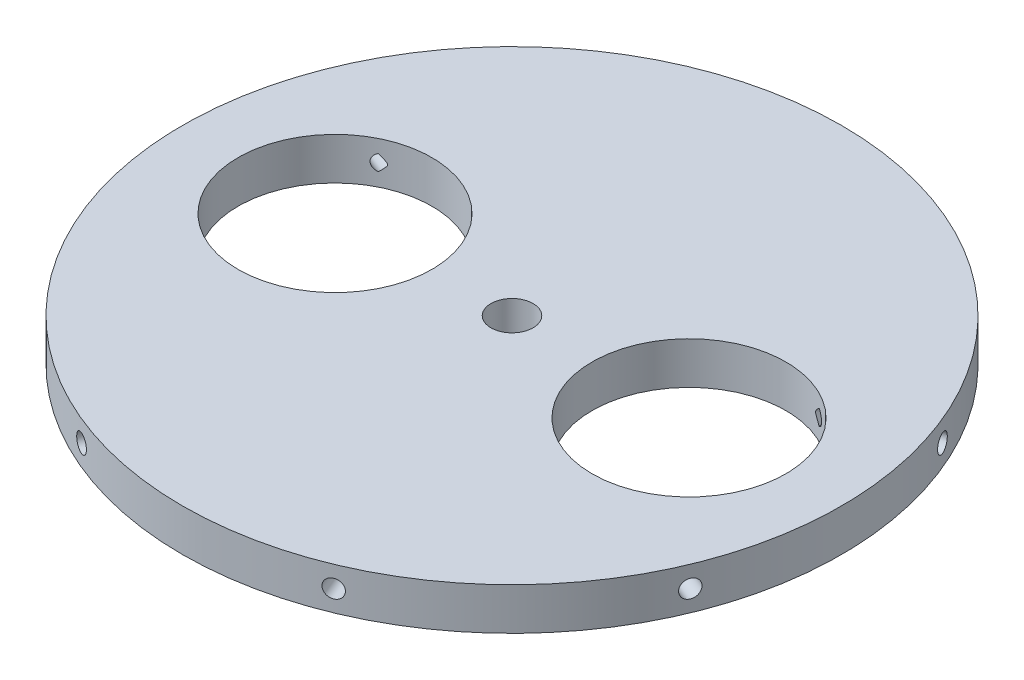
SolidWorks part; units mm, degrees
ref_plane "Front Plane" through (0, 0, 0) normal (0, 0, 1) x (1, 0, 0)
ref_plane "Top Plane" through (0, 0, 0) normal (0, 1, 0) x (1, 0, 0)
ref_plane "Right Plane" through (0, 0, 0) normal (1, 0, 0) x (0, 0, -1)
sketch "Sketch2" plane through (0, 0, 0) normal (0, 1, 0) x (1, 0, 0)
  circle A0 centre (0, 0) radius 49.657
  dimension "D1" = 99.314
extrude "Boss-Extrude1" add sketch "Sketch2" along normal blind 6.35
sketch "Sketch3" plane through (0, 6.35, 0) normal (0, 1, 0) x (1, 0, 0)
  line L0 (-56.3402, 0) -> (60.062, 0) construction
  line L1 (0, -54.5435) -> (0, 52.8751) construction
  circle A0 centre (26.67, 0) radius 14.605
  circle A1 centre (-26.67, 0) radius 14.605
  dimension "D1" = 29.21
  dimension "D2" = 29.21
  dimension "D3" = 26.67
  dimension "D4" = 26.67
extrude "Cut-Extrude1" cut sketch "Sketch3" against normal blind 6.35
sketch "Sketch5" plane through (0, 0, 0) normal (0, -1, 0) x (1, 0, 0)
  circle A0 centre (0, 0) radius 3.175
  dimension "D1" = 6.35
extrude "Cut-Extrude2" cut sketch "Sketch5" against normal blind 6.35
ref_plane "Plane1" through (-19.0029, 0, 45.8771) normal (-0.3827, 0, 0.9239) x (0, -1, 0)
hole_wizard "#6-32 Tapped Hole1" positions "Sketch7" profile "Sketch8" tap size "#6-32" standard "DME"
sketch "Sketch7" plane through (-19.0029, 0, 45.8771) normal (-0.3827, 0, 0.9239) x (0, -1, 0)
  line L0 (-6.35, -52.0515) -> (-6.35, 55.49) construction
  point P0 (-3.175, 0)
  dimension "D1" = 3.175
sketch "Sketch8" plane through (-19.0029, 3.175, 45.8771) normal (0, 1, 0) x (0.9239, 0, 0.3827)
  line L0 (0, 0) -> (0, 14.7827)
  line L1 (0, 14.7827) -> (1.3525, 13.97)
  line L2 (1.3525, 13.97) -> (1.3525, 0)
  line L5 (1.3525, 0) -> (0, 0)
  line L10 (0, 14.7827) -> (-1.3526, 13.97) construction
  line L11 (0, -6.35) -> (0, 107.95) construction
  dimension "Tap Drill Dia." = 2.7051
  dimension "Tap Drill Depth" = 13.97
  dimension "Drill Angle" = 118
cosmetic thread "Hole Thread1" parameters "D1"=9.906, "D2"=3.5052
ref_axis "Axis1" through (0, -0.3175, 0) along (0, 1, 0)
pattern_circular "CirPattern1" count 8 over 360 about axis through (0, -0.3175, 0) along (0, 1, 0) of "#6-32 Tapped Hole1"
cosmetic thread "Hole Thread2" parameters "D1"=9.906, "D2"=3.5052
cosmetic thread "Hole Thread3" parameters "D1"=9.906, "D2"=3.5052
cosmetic thread "Hole Thread4" parameters "D1"=9.906, "D2"=3.5052
cosmetic thread "Hole Thread5" parameters "D1"=9.906, "D2"=3.5052
cosmetic thread "Hole Thread6" parameters "D1"=9.906, "D2"=3.5052
cosmetic thread "Hole Thread7" parameters "D1"=9.906, "D2"=3.5052
cosmetic thread "Hole Thread8" parameters "D1"=9.906, "D2"=3.5052
